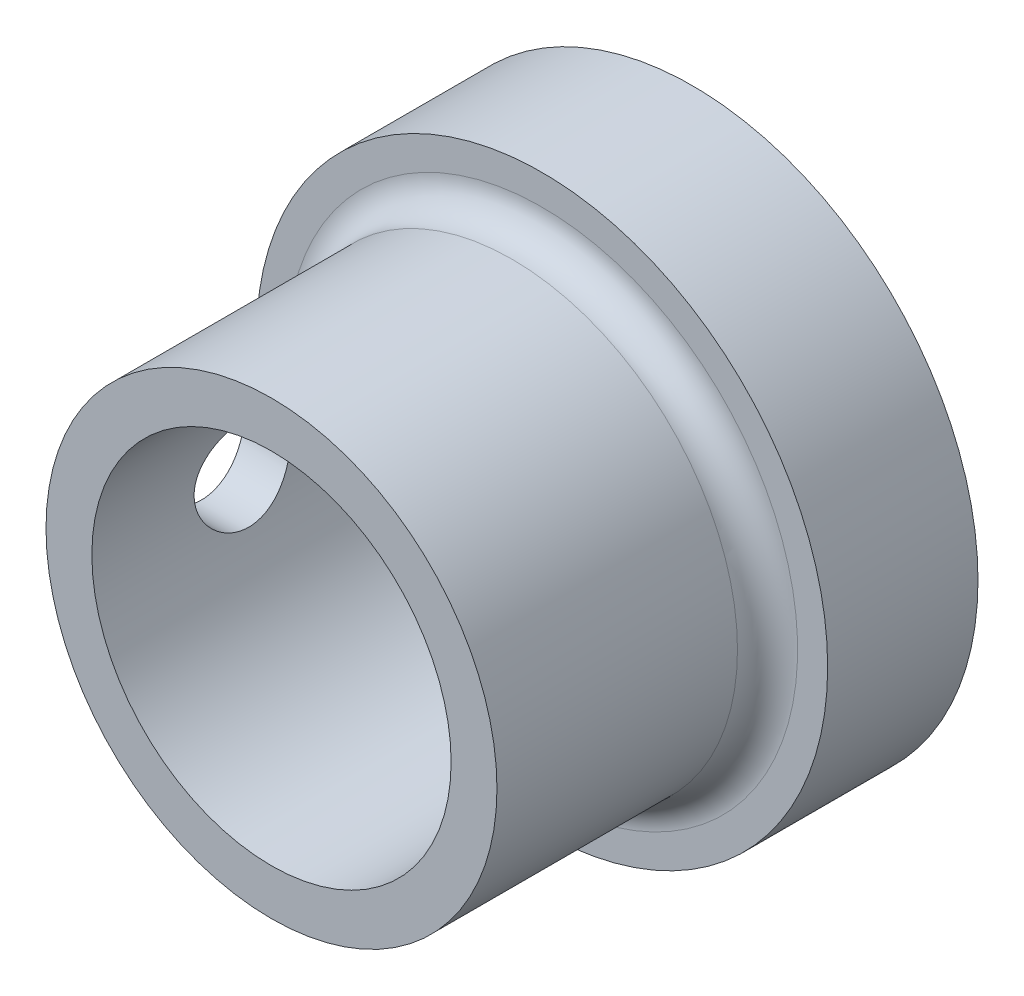
SolidWorks part; units mm, degrees
ref_plane "Front Plane" through (0, 0, 0) normal (0, 0, 1) x (1, 0, 0)
ref_plane "Top Plane" through (0, 0, 0) normal (0, 1, 0) x (1, 0, 0)
ref_plane "Right Plane" through (0, 0, 0) normal (1, 0, 0) x (0, 0, -1)
sketch "Sketch2" plane through (0, 0, 0) normal (0, 0, 1) x (1, 0, 0)
  circle A0 centre (0, 0) radius 7.5
  circle A1 centre (0, 0) radius 5.975
  dimension "D1" = 15
  dimension "D2" = 11.95
extrude "Boss-Extrude1" add sketch "Sketch2" along normal blind 9
sketch "Sketch3" plane through (0, 0, 0) normal (0, 0, -1) x (-1, 0, 0)
  circle A0 centre (0, 0) radius 9.5
  dimension "D1" = 19
extrude "Boss-Extrude2" add sketch "Sketch3" along normal blind 5
sketch "Sketch4" plane through (0, 0, 0) normal (0, 0, 1) x (1, 0, 0)
  circle A0 centre (0, 0) radius 5.975
  dimension "D1" = 11.95
extrude "Cut-Extrude1" cut sketch "Sketch4" against normal blind 5
ref_plane "Plane2" through (-7.5, 0, 0) normal (-1, 0, 0) x (0, 0, 1)
sketch "Sketch5" plane through (-7.5, 0, 0) normal (-1, 0, 0) x (0, 0, 1)
  line L0 (18.0656, 0) -> (-16.388, 0) construction
  line L1 (4, 8.5876) -> (4, -9.4399) construction
  line L2 (9, -7.5) -> (9, 7.5) construction
  circle A0 centre (4, 0) radius 1.6
  dimension "D2" = 3.2
  dimension "D1" = 5
extrude "Cut-Extrude2" cut sketch "Sketch5" against normal blind 12
fillet "Fillet1" radius 1 1 edges at (7.5, 0, 0)
